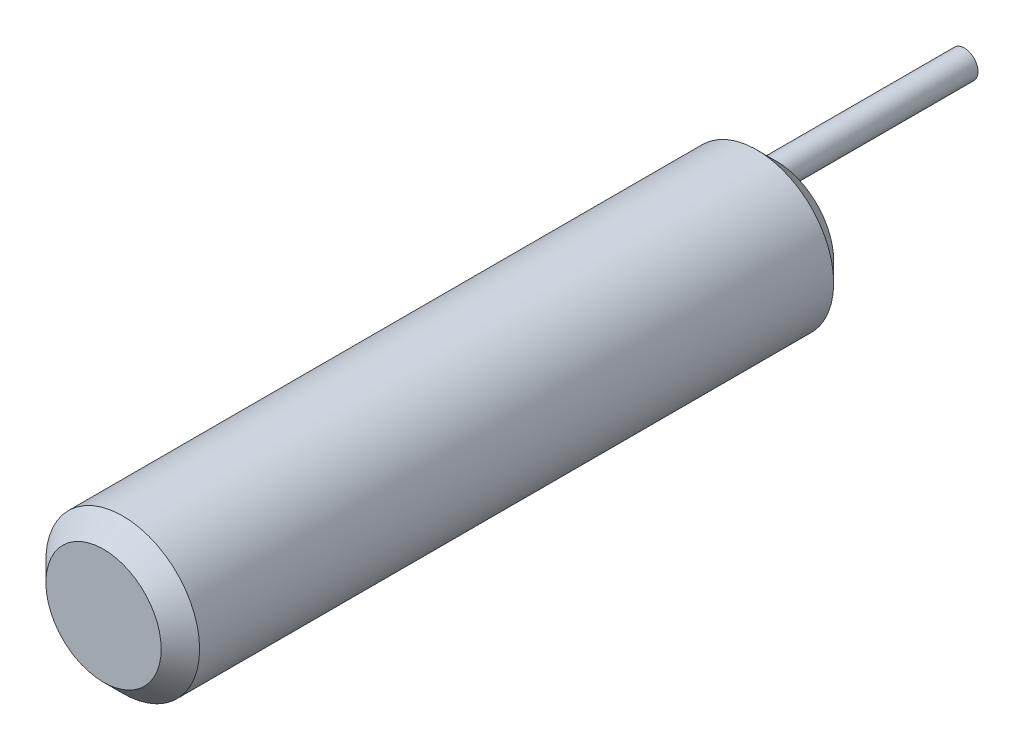
SolidWorks part; units mm, degrees
ref_plane "Спереди" through (0, 0, 0) normal (0, 0, 1) x (1, 0, 0)
ref_plane "Сверху" through (0, 0, 0) normal (0, 1, 0) x (1, 0, 0)
ref_plane "Справа" through (0, 0, 0) normal (1, 0, 0) x (0, 0, -1)
sketch "Эскиз1" plane through (0, 0, 0) normal (0, 0, 1) x (1, 0, 0)
  circle A0 centre (0, 0) radius 4
  dimension "D1" = 8
extrude "Бобышка-Вытянуть1" add sketch "Эскиз1" along normal blind 35
chamfer "Фаска1" distance 1 angle 45 2 edges at (4, 0, 0) (4, 0, 35)
sketch "Эскиз2" plane through (0, 0, 0) normal (0, 0, -1) x (-1, 0, 0)
  circle A0 centre (0.2002, 2.2781) radius 0.7132
extrude "Бобышка-Вытянуть2" add sketch "Эскиз2" along normal blind 10
